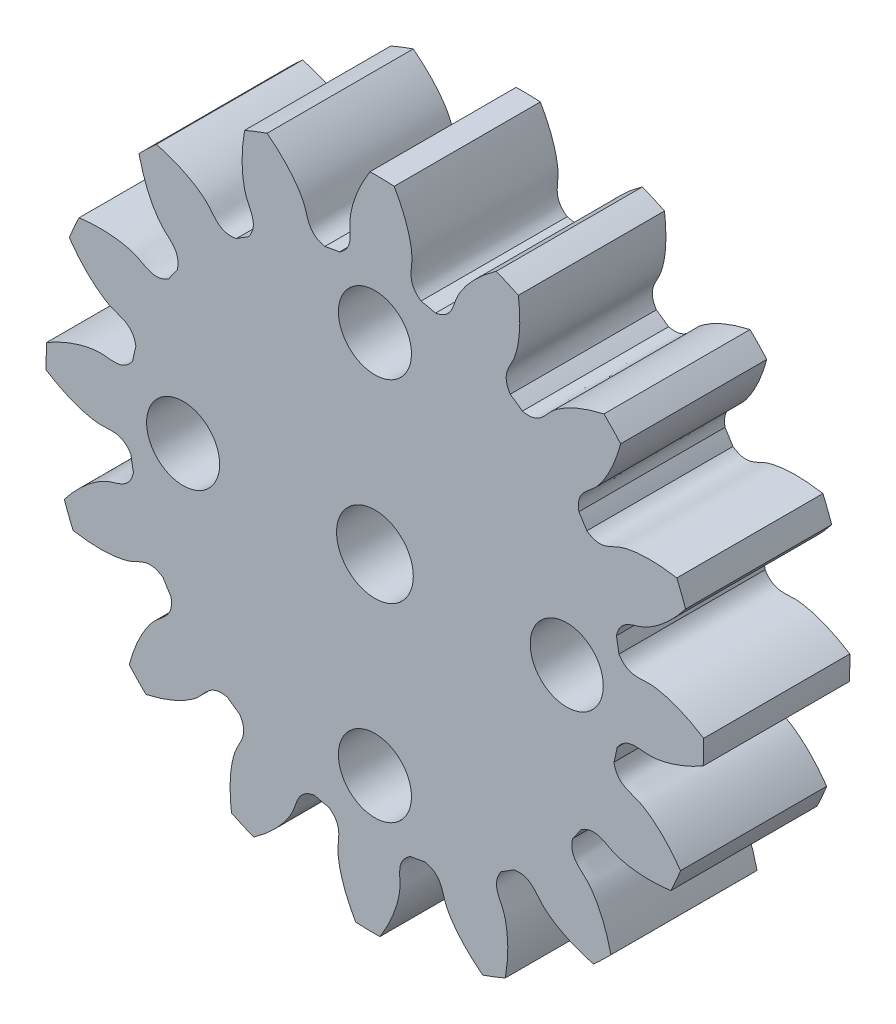
SolidWorks part; units mm, degrees
ref_plane "前视基准面" through (0, 0, 0) normal (0, 0, 1) x (1, 0, 0)
ref_plane "上视基准面" through (0, 0, 0) normal (0, 1, 0) x (1, 0, 0)
ref_plane "右视基准面" through (0, 0, 0) normal (1, 0, 0) x (0, 0, -1)
sketch "草图1" plane through (0, 0, 0) normal (0, 0, 1) x (1, 0, 0)
  circle A135 centre (26.7499, -4.2787) radius 1
  circle A136 centre (31.9999, 0.9713) radius 1
  circle A137 centre (26.7499, 6.2213) radius 1
  circle A138 centre (21.4999, 0.9713) radius 1
  arc A139 (20.7698, 7.6973) -> (20.2911, 7.2391) centre (26.7499, 0.9713) ccw
  arc A140 (21.3397, 5.0078) -> (21.1065, 4.6746) centre (26.7499, 0.9713) ccw
  arc A141 (18.6511, 4.8969) -> (18.3842, 4.2903) centre (26.7499, 0.9713) ccw
  arc A142 (20.2069, 2.6302) -> (20.1188, 2.2331) centre (26.7499, 0.9713) ccw
  arc A143 (17.7653, 1.4988) -> (17.7509, 0.8362) centre (26.7499, 0.9713) ccw
  arc A144 (20.0701, 0) -> (20.1407, -0.4005) centre (26.7499, 0.9713) ccw
  arc A145 (18.2474, -1.9796) -> (18.4876, -2.5972) centre (26.7499, 0.9713) ccw
  arc A146 (20.9503, -2.4823) -> (21.1688, -2.8253) centre (26.7499, 0.9713) ccw
  arc A147 (20.0239, -5.0087) -> (20.4821, -5.4874) centre (26.7499, 0.9713) ccw
  arc A148 (22.7134, -4.4388) -> (23.0466, -4.6721) centre (26.7499, 0.9713) ccw
  arc A149 (22.8243, -7.1274) -> (23.4309, -7.3943) centre (26.7499, 0.9713) ccw
  arc A150 (25.091, -5.5717) -> (25.4881, -5.6597) centre (26.7499, 0.9713) ccw
  arc A151 (26.2224, -8.0132) -> (26.8849, -8.0277) centre (26.7499, 0.9713) ccw
  arc A152 (27.7212, -5.7084) -> (28.1217, -5.6378) centre (26.7499, 0.9713) ccw
  arc A153 (29.7008, -7.5312) -> (30.3184, -7.291) centre (26.7499, 0.9713) ccw
  arc A154 (30.2035, -4.8283) -> (30.5465, -4.6097) centre (26.7499, 0.9713) ccw
  arc A155 (32.7299, -5.7547) -> (33.2086, -5.2964) centre (26.7499, 0.9713) ccw
  arc A156 (32.16, -3.0651) -> (32.3933, -2.732) centre (26.7499, 0.9713) ccw
  arc A157 (34.8486, -2.9542) -> (35.1155, -2.3476) centre (26.7499, 0.9713) ccw
  arc A158 (33.2929, -0.6875) -> (33.3809, -0.2904) centre (26.7499, 0.9713) ccw
  arc A159 (35.7344, 0.4438) -> (35.7489, 1.1064) centre (26.7499, 0.9713) ccw
  arc A160 (33.4296, 1.9426) -> (33.359, 2.3432) centre (26.7499, 0.9713) ccw
  arc A161 (35.2523, 3.9222) -> (35.0122, 4.5399) centre (26.7499, 0.9713) ccw
  arc A162 (32.5494, 4.4249) -> (32.3309, 4.768) centre (26.7499, 0.9713) ccw
  arc A163 (33.4759, 6.9514) -> (33.0176, 7.4301) centre (26.7499, 0.9713) ccw
  arc A164 (30.7863, 6.3814) -> (30.4532, 6.6147) centre (26.7499, 0.9713) ccw
  arc A165 (30.6754, 9.0701) -> (30.0688, 9.337) centre (26.7499, 0.9713) ccw
  arc A166 (28.4087, 7.5143) -> (28.0116, 7.6023) centre (26.7499, 0.9713) ccw
  arc A167 (27.2773, 9.9559) -> (26.6148, 9.9703) centre (26.7499, 0.9713) ccw
  arc A168 (25.7785, 7.6511) -> (25.378, 7.5804) centre (26.7499, 0.9713) ccw
  arc A169 (23.799, 9.4738) -> (23.1813, 9.2336) centre (26.7499, 0.9713) ccw
  arc A170 (23.2963, 6.7709) -> (22.9532, 6.5524) centre (26.7499, 0.9713) ccw
  circle A171 centre (26.7499, 0.9713) radius 1.05
  spline S32 degree 3 poles (22.9532, 6.5524) (22.485, 6.4713) (22.3632, 6.7975) (22.1228, 7.0302) (22.0876, 7.0622) (22.0369, 7.1047) (21.9751, 7.1526) (21.9016, 7.2049) (21.816, 7.2609) (21.7179, 7.3196) (21.607, 7.38) (21.483, 7.4414) (21.3456, 7.5026) (21.1948, 7.5627) (21.0303, 7.6208) (20.887, 7.6651) (20.7985, 7.6896) (20.7698, 7.6973) knots 0 0 0 0 0.200958 0.205848 0.217584 0.231929 0.248881 0.268441 0.29061 0.315386 0.342771 0.372764 0.405364 0.440573 0.47839 0.518814 0.53812 0.53812 0.53812 0.53812
  spline S33 degree 3 poles (20.2911, 7.2391) (20.311, 7.1494) (20.3475, 7.0039) (20.407, 6.8086) (20.4605, 6.6553) (20.5157, 6.5154) (20.5716, 6.3888) (20.6272, 6.2754) (20.6815, 6.1748) (20.7337, 6.0869) (20.7827, 6.0112) (20.8279, 5.9473) (20.8682, 5.8948) (20.8986, 5.8582) (21.1206, 5.608) (21.4412, 5.472) (21.3397, 5.0078) knots 0 0 0 0 0.059731 0.097548 0.132756 0.165357 0.195349 0.222734 0.247511 0.269679 0.289239 0.306192 0.320536 0.332272 0.337162 0.53812 0.53812 0.53812 0.53812
  spline S34 degree 3 poles (21.1065, 4.6746) (20.7049, 4.4205) (20.4675, 4.6753) (20.1564, 4.7983) (20.1116, 4.8144) (20.0485, 4.8343) (19.9731, 4.8548) (19.8851, 4.8751) (19.7846, 4.894) (19.6716, 4.9107) (19.546, 4.9241) (19.4079, 4.9333) (19.2576, 4.9373) (19.0952, 4.9352) (18.921, 4.9259) (18.7717, 4.9119) (18.6805, 4.9008) (18.6511, 4.8969) knots 0 0 0 0 0.200958 0.205848 0.217584 0.231929 0.248881 0.268441 0.29061 0.315386 0.342771 0.372764 0.405364 0.440573 0.47839 0.518814 0.53812 0.53812 0.53812 0.53812
  spline S35 degree 3 poles (18.3842, 4.2903) (18.4369, 4.2151) (18.5263, 4.0946) (18.656, 3.937) (18.7641, 3.8158) (18.8686, 3.7077) (18.9687, 3.6121) (19.0634, 3.5286) (19.1521, 3.4565) (19.234, 3.3952) (19.3083, 3.344) (19.3744, 3.3023) (19.4317, 3.2692) (19.4739, 3.2471) (19.7747, 3.1008) (20.1229, 3.0979) (20.2069, 2.6302) knots 0 0 0 0 0.059731 0.097548 0.132756 0.165357 0.195349 0.222734 0.247511 0.269679 0.289239 0.306192 0.320536 0.332272 0.337162 0.53812 0.53812 0.53812 0.53812
  spline S36 degree 3 poles (20.1188, 2.2331) (19.8451, 1.8446) (19.5283, 1.9892) (19.1938, 1.9838) (19.1462, 1.9815) (19.0803, 1.9757) (19.0028, 1.9659) (18.9138, 1.9509) (18.8137, 1.9299) (18.7029, 1.9021) (18.5817, 1.8664) (18.4506, 1.8221) (18.3102, 1.7683) (18.161, 1.7041) (18.0036, 1.6289) (17.871, 1.5588) (17.791, 1.5136) (17.7653, 1.4988) knots 0 0 0 0 0.200958 0.205848 0.217584 0.231929 0.248881 0.268441 0.29061 0.315386 0.342771 0.372764 0.405364 0.440573 0.47839 0.518814 0.53812 0.53812 0.53812 0.53812
  spline S37 degree 3 poles (17.7509, 0.8362) (17.8283, 0.7869) (17.9571, 0.7099) (18.1372, 0.6139) (18.2835, 0.5433) (18.4214, 0.4834) (18.5504, 0.4334) (18.6699, 0.3925) (18.7794, 0.3598) (18.8785, 0.3345) (18.9668, 0.3157) (19.0438, 0.3024) (19.1094, 0.2938) (19.1568, 0.2894) (19.4908, 0.2695) (19.8136, 0.4) (20.0701, 0) knots 0 0 0 0 0.059731 0.097548 0.132756 0.165357 0.195349 0.222734 0.247511 0.269679 0.289239 0.306192 0.320536 0.332272 0.337162 0.53812 0.53812 0.53812 0.53812
  spline S38 degree 3 poles (20.1407, -0.4005) (20.0365, -0.8642) (19.6885, -0.8519) (19.3815, -0.9849) (19.3385, -1.0052) (19.2798, -1.0357) (19.2119, -1.0745) (19.1354, -1.1224) (19.051, -1.1801) (18.9592, -1.2482) (18.8609, -1.3276) (18.7568, -1.4187) (18.6477, -1.5221) (18.5344, -1.6385) (18.4177, -1.7682) (18.322, -1.8837) (18.2655, -1.956) (18.2474, -1.9796) knots 0 0 0 0 0.200958 0.205848 0.217584 0.231929 0.248881 0.268441 0.29061 0.315386 0.342771 0.372764 0.405364 0.440573 0.47839 0.518814 0.53812 0.53812 0.53812 0.53812
  spline S39 degree 3 poles (18.4876, -2.5972) (18.578, -2.6132) (18.7264, -2.6351) (18.9296, -2.6548) (19.0917, -2.6641) (19.2421, -2.6666) (19.3804, -2.6635) (19.5065, -2.6555) (19.6202, -2.6438) (19.7214, -2.6293) (19.8101, -2.6129) (19.8864, -2.5957) (19.9503, -2.5785) (19.9958, -2.5644) (20.3119, -2.4551) (20.5602, -2.2109) (20.9503, -2.4823) knots 0 0 0 0 0.059731 0.097548 0.132756 0.165357 0.195349 0.222734 0.247511 0.269679 0.289239 0.306192 0.320536 0.332272 0.337162 0.53812 0.53812 0.53812 0.53812
  spline S40 degree 3 poles (21.1688, -2.8253) (21.2499, -3.2936) (20.9237, -3.4154) (20.691, -3.6557) (20.659, -3.6909) (20.6165, -3.7416) (20.5686, -3.8035) (20.5163, -3.877) (20.4603, -3.9626) (20.4016, -4.0606) (20.3412, -4.1715) (20.2798, -4.2956) (20.2186, -4.4329) (20.1585, -4.5838) (20.1004, -4.7483) (20.0561, -4.8916) (20.0315, -4.98) (20.0239, -5.0087) knots 0 0 0 0 0.200958 0.205848 0.217584 0.231929 0.248881 0.268441 0.29061 0.315386 0.342771 0.372764 0.405364 0.440573 0.47839 0.518814 0.53812 0.53812 0.53812 0.53812
  spline S41 degree 3 poles (20.4821, -5.4874) (20.5718, -5.4676) (20.7173, -5.431) (20.9126, -5.3715) (21.0659, -5.318) (21.2058, -5.2628) (21.3324, -5.207) (21.4458, -5.1514) (21.5463, -5.097) (21.6343, -5.0449) (21.71, -4.9958) (21.7739, -4.9507) (21.8264, -4.9104) (21.863, -4.8799) (22.1132, -4.6579) (22.2491, -4.3374) (22.7134, -4.4388) knots 0 0 0 0 0.059731 0.097548 0.132756 0.165357 0.195349 0.222734 0.247511 0.269679 0.289239 0.306192 0.320536 0.332272 0.337162 0.53812 0.53812 0.53812 0.53812
  spline S42 degree 3 poles (23.0466, -4.6721) (23.3007, -5.0736) (23.0459, -5.311) (22.9229, -5.6221) (22.9068, -5.6669) (22.8869, -5.73) (22.8663, -5.8055) (22.8461, -5.8934) (22.8272, -5.9939) (22.8105, -6.107) (22.7971, -6.2326) (22.7879, -6.3706) (22.7839, -6.5209) (22.786, -6.6833) (22.7953, -6.8575) (22.8093, -7.0069) (22.8204, -7.098) (22.8243, -7.1274) knots 0 0 0 0 0.200958 0.205848 0.217584 0.231929 0.248881 0.268441 0.29061 0.315386 0.342771 0.372764 0.405364 0.440573 0.47839 0.518814 0.53812 0.53812 0.53812 0.53812
  spline S43 degree 3 poles (23.4309, -7.3943) (23.5061, -7.3417) (23.6266, -7.2522) (23.7842, -7.1225) (23.9054, -7.0144) (24.0135, -6.9099) (24.1091, -6.8099) (24.1926, -6.7151) (24.2647, -6.6264) (24.326, -6.5446) (24.3772, -6.4702) (24.4189, -6.4041) (24.452, -6.3468) (24.4741, -6.3047) (24.6204, -6.0038) (24.6233, -5.6556) (25.091, -5.5717) knots 0 0 0 0 0.059731 0.097548 0.132756 0.165357 0.195349 0.222734 0.247511 0.269679 0.289239 0.306192 0.320536 0.332272 0.337162 0.53812 0.53812 0.53812 0.53812
  spline S44 degree 3 poles (25.4881, -5.6597) (25.8765, -5.9334) (25.732, -6.2503) (25.7374, -6.5847) (25.7397, -6.6323) (25.7454, -6.6982) (25.7553, -6.7758) (25.7703, -6.8648) (25.7913, -6.9648) (25.8191, -7.0757) (25.8548, -7.1969) (25.8991, -7.3279) (25.9529, -7.4683) (26.0171, -7.6176) (26.0923, -7.7749) (26.1624, -7.9076) (26.2076, -7.9875) (26.2224, -8.0132) knots 0 0 0 0 0.200958 0.205848 0.217584 0.231929 0.248881 0.268441 0.29061 0.315386 0.342771 0.372764 0.405364 0.440573 0.47839 0.518814 0.53812 0.53812 0.53812 0.53812
  spline S45 degree 3 poles (26.8849, -8.0277) (26.9343, -7.9502) (27.0113, -7.8215) (27.1073, -7.6413) (27.1779, -7.4951) (27.2378, -7.3571) (27.2878, -7.2281) (27.3287, -7.1086) (27.3614, -6.9991) (27.3867, -6.9) (27.4055, -6.8118) (27.4188, -6.7347) (27.4274, -6.6691) (27.4317, -6.6217) (27.4517, -6.2878) (27.3212, -5.965) (27.7212, -5.7084) knots 0 0 0 0 0.059731 0.097548 0.132756 0.165357 0.195349 0.222734 0.247511 0.269679 0.289239 0.306192 0.320536 0.332272 0.337162 0.53812 0.53812 0.53812 0.53812
  spline S46 degree 3 poles (28.1217, -5.6378) (28.5854, -5.7421) (28.5731, -6.0901) (28.7061, -6.397) (28.7264, -6.4401) (28.7569, -6.4988) (28.7957, -6.5667) (28.8436, -6.6431) (28.9013, -6.7276) (28.9694, -6.8193) (29.0487, -6.9176) (29.1399, -7.0218) (29.2433, -7.1309) (29.3597, -7.2442) (29.4894, -7.3608) (29.6049, -7.4565) (29.6772, -7.5131) (29.7008, -7.5312) knots 0 0 0 0 0.200958 0.205848 0.217584 0.231929 0.248881 0.268441 0.29061 0.315386 0.342771 0.372764 0.405364 0.440573 0.47839 0.518814 0.53812 0.53812 0.53812 0.53812
  spline S47 degree 3 poles (30.3184, -7.291) (30.3344, -7.2005) (30.3563, -7.0521) (30.376, -6.849) (30.3853, -6.6868) (30.3878, -6.5364) (30.3847, -6.3981) (30.3767, -6.2721) (30.365, -6.1584) (30.3505, -6.0572) (30.3341, -5.9684) (30.3169, -5.8921) (30.2997, -5.8282) (30.2856, -5.7828) (30.1763, -5.4666) (29.9321, -5.2183) (30.2035, -4.8283) knots 0 0 0 0 0.059731 0.097548 0.132756 0.165357 0.195349 0.222734 0.247511 0.269679 0.289239 0.306192 0.320536 0.332272 0.337162 0.53812 0.53812 0.53812 0.53812
  spline S48 degree 3 poles (30.5465, -4.6097) (31.0147, -4.5286) (31.1366, -4.8548) (31.3769, -5.0875) (31.4121, -5.1196) (31.4628, -5.1621) (31.5247, -5.21) (31.5981, -5.2623) (31.6837, -5.3182) (31.7818, -5.3769) (31.8927, -5.4374) (32.0167, -5.4987) (32.1541, -5.5599) (32.305, -5.6201) (32.4694, -5.6782) (32.6128, -5.7224) (32.7012, -5.747) (32.7299, -5.7547) knots 0 0 0 0 0.200958 0.205848 0.217584 0.231929 0.248881 0.268441 0.29061 0.315386 0.342771 0.372764 0.405364 0.440573 0.47839 0.518814 0.53812 0.53812 0.53812 0.53812
  spline S49 degree 3 poles (33.2086, -5.2964) (33.1887, -5.2068) (33.1522, -5.0613) (33.0927, -4.866) (33.0392, -4.7127) (32.984, -4.5728) (32.9281, -4.4462) (32.8726, -4.3328) (32.8182, -4.2322) (32.7661, -4.1443) (32.717, -4.0685) (32.6719, -4.0047) (32.6316, -3.9522) (32.6011, -3.9156) (32.3791, -3.6653) (32.0585, -3.5294) (32.16, -3.0651) knots 0 0 0 0 0.059731 0.097548 0.132756 0.165357 0.195349 0.222734 0.247511 0.269679 0.289239 0.306192 0.320536 0.332272 0.337162 0.53812 0.53812 0.53812 0.53812
  spline S50 degree 3 poles (32.3933, -2.732) (32.7948, -2.4779) (33.0322, -2.7326) (33.3433, -2.8556) (33.3881, -2.8717) (33.4512, -2.8916) (33.5267, -2.9122) (33.6146, -2.9324) (33.7151, -2.9514) (33.8282, -2.968) (33.9538, -2.9815) (34.0918, -2.9907) (34.2421, -2.9947) (34.4045, -2.9925) (34.5787, -2.9832) (34.7281, -2.9693) (34.8192, -2.9581) (34.8486, -2.9542) knots 0 0 0 0 0.200958 0.205848 0.217584 0.231929 0.248881 0.268441 0.29061 0.315386 0.342771 0.372764 0.405364 0.440573 0.47839 0.518814 0.53812 0.53812 0.53812 0.53812
  spline S51 degree 3 poles (35.1155, -2.3476) (35.0629, -2.2724) (34.9734, -2.152) (34.8437, -1.9944) (34.7356, -1.8732) (34.6311, -1.765) (34.531, -1.6695) (34.4363, -1.5859) (34.3476, -1.5138) (34.2658, -1.4526) (34.1914, -1.4014) (34.1253, -1.3596) (34.068, -1.3266) (34.0258, -1.3044) (33.725, -1.1582) (33.3768, -1.1553) (33.2929, -0.6875) knots 0 0 0 0 0.059731 0.097548 0.132756 0.165357 0.195349 0.222734 0.247511 0.269679 0.289239 0.306192 0.320536 0.332272 0.337162 0.53812 0.53812 0.53812 0.53812
  spline S52 degree 3 poles (33.3809, -0.2904) (33.6546, 0.098) (33.9714, -0.0465) (34.3059, -0.0411) (34.3535, -0.0389) (34.4194, -0.0331) (34.497, -0.0232) (34.5859, -0.0083) (34.686, 0.0127) (34.7969, 0.0406) (34.9181, 0.0762) (35.0491, 0.1206) (35.1895, 0.1744) (35.3387, 0.2385) (35.4961, 0.3138) (35.6288, 0.3838) (35.7087, 0.429) (35.7344, 0.4438) knots 0 0 0 0 0.200958 0.205848 0.217584 0.231929 0.248881 0.268441 0.29061 0.315386 0.342771 0.372764 0.405364 0.440573 0.47839 0.518814 0.53812 0.53812 0.53812 0.53812
  spline S53 degree 3 poles (35.7489, 1.1064) (35.6714, 1.1557) (35.5427, 1.2328) (35.3625, 1.3288) (35.2163, 1.3994) (35.0783, 1.4593) (34.9493, 1.5093) (34.8298, 1.5502) (34.7203, 1.5829) (34.6212, 1.6082) (34.533, 1.627) (34.4559, 1.6403) (34.3903, 1.6489) (34.3429, 1.6532) (34.009, 1.6732) (33.6862, 1.5426) (33.4296, 1.9426) knots 0 0 0 0 0.059731 0.097548 0.132756 0.165357 0.195349 0.222734 0.247511 0.269679 0.289239 0.306192 0.320536 0.332272 0.337162 0.53812 0.53812 0.53812 0.53812
  spline S54 degree 3 poles (33.359, 2.3432) (33.4633, 2.8068) (33.8112, 2.7945) (34.1182, 2.9275) (34.1613, 2.9478) (34.22, 2.9784) (34.2879, 3.0172) (34.3643, 3.0651) (34.4488, 3.1227) (34.5405, 3.1909) (34.6388, 3.2702) (34.7429, 3.3613) (34.8521, 3.4648) (34.9654, 3.5811) (35.082, 3.7109) (35.1777, 3.8263) (35.2343, 3.8987) (35.2523, 3.9222) knots 0 0 0 0 0.200958 0.205848 0.217584 0.231929 0.248881 0.268441 0.29061 0.315386 0.342771 0.372764 0.405364 0.440573 0.47839 0.518814 0.53812 0.53812 0.53812 0.53812
  spline S55 degree 3 poles (35.0122, 4.5399) (34.9217, 4.5558) (34.7733, 4.5777) (34.5701, 4.5975) (34.408, 4.6067) (34.2576, 4.6093) (34.1193, 4.6061) (33.9932, 4.5982) (33.8796, 4.5865) (33.7783, 4.5719) (33.6896, 4.5555) (33.6133, 4.5383) (33.5494, 4.5212) (33.504, 4.507) (33.1878, 4.3977) (32.9395, 4.1536) (32.5494, 4.4249) knots 0 0 0 0 0.059731 0.097548 0.132756 0.165357 0.195349 0.222734 0.247511 0.269679 0.289239 0.306192 0.320536 0.332272 0.337162 0.53812 0.53812 0.53812 0.53812
  spline S56 degree 3 poles (32.3309, 4.768) (32.2498, 5.2362) (32.576, 5.358) (32.8087, 5.5984) (32.8407, 5.6336) (32.8833, 5.6843) (32.9311, 5.7461) (32.9835, 5.8196) (33.0394, 5.9052) (33.0981, 6.0033) (33.1586, 6.1142) (33.2199, 6.2382) (33.2811, 6.3756) (33.3413, 6.5264) (33.3994, 6.6909) (33.4436, 6.8342) (33.4682, 6.9227) (33.4759, 6.9514) knots 0 0 0 0 0.200958 0.205848 0.217584 0.231929 0.248881 0.268441 0.29061 0.315386 0.342771 0.372764 0.405364 0.440573 0.47839 0.518814 0.53812 0.53812 0.53812 0.53812
  spline S57 degree 3 poles (33.0176, 7.4301) (32.928, 7.4102) (32.7824, 7.3737) (32.5872, 7.3142) (32.4338, 7.2606) (32.2939, 7.2055) (32.1674, 7.1496) (32.0539, 7.094) (31.9534, 7.0397) (31.8654, 6.9875) (31.7897, 6.9384) (31.7259, 6.8933) (31.6734, 6.853) (31.6368, 6.8226) (31.3865, 6.6006) (31.2506, 6.28) (30.7863, 6.3814) knots 0 0 0 0 0.059731 0.097548 0.132756 0.165357 0.195349 0.222734 0.247511 0.269679 0.289239 0.306192 0.320536 0.332272 0.337162 0.53812 0.53812 0.53812 0.53812
  spline S58 degree 3 poles (30.4532, 6.6147) (30.1991, 7.0163) (30.4538, 7.2537) (30.5768, 7.5648) (30.5929, 7.6096) (30.6128, 7.6727) (30.6334, 7.7481) (30.6536, 7.8361) (30.6726, 7.9365) (30.6892, 8.0496) (30.7027, 8.1752) (30.7119, 8.3133) (30.7159, 8.4636) (30.7137, 8.626) (30.7044, 8.8002) (30.6905, 8.9495) (30.6793, 9.0407) (30.6754, 9.0701) knots 0 0 0 0 0.200958 0.205848 0.217584 0.231929 0.248881 0.268441 0.29061 0.315386 0.342771 0.372764 0.405364 0.440573 0.47839 0.518814 0.53812 0.53812 0.53812 0.53812
  spline S59 degree 3 poles (30.0688, 9.337) (29.9936, 9.2843) (29.8732, 9.1949) (29.7155, 9.0652) (29.5944, 8.9571) (29.4862, 8.8525) (29.3907, 8.7525) (29.3071, 8.6577) (29.235, 8.5691) (29.1737, 8.4872) (29.1226, 8.4129) (29.0808, 8.3468) (29.0478, 8.2895) (29.0256, 8.2473) (28.8794, 7.9465) (28.8764, 7.5983) (28.4087, 7.5143) knots 0 0 0 0 0.059731 0.097548 0.132756 0.165357 0.195349 0.222734 0.247511 0.269679 0.289239 0.306192 0.320536 0.332272 0.337162 0.53812 0.53812 0.53812 0.53812
  spline S60 degree 3 poles (28.0116, 7.6023) (27.6232, 7.8761) (27.7677, 8.1929) (27.7623, 8.5274) (27.76, 8.5749) (27.7543, 8.6409) (27.7444, 8.7184) (27.7294, 8.8074) (27.7085, 8.9075) (27.6806, 9.0183) (27.645, 9.1395) (27.6006, 9.2706) (27.5468, 9.411) (27.4827, 9.5602) (27.4074, 9.7176) (27.3374, 9.8502) (27.2922, 9.9301) (27.2773, 9.9559) knots 0 0 0 0 0.200958 0.205848 0.217584 0.231929 0.248881 0.268441 0.29061 0.315386 0.342771 0.372764 0.405364 0.440573 0.47839 0.518814 0.53812 0.53812 0.53812 0.53812
  spline S61 degree 3 poles (26.6148, 9.9703) (26.5655, 9.8929) (26.4884, 9.7641) (26.3924, 9.584) (26.3218, 9.4377) (26.2619, 9.2998) (26.2119, 9.1708) (26.171, 9.0513) (26.1383, 8.9418) (26.113, 8.8427) (26.0942, 8.7544) (26.0809, 8.6774) (26.0723, 8.6118) (26.068, 8.5643) (26.048, 8.2304) (26.1786, 7.9076) (25.7785, 7.6511) knots 0 0 0 0 0.059731 0.097548 0.132756 0.165357 0.195349 0.222734 0.247511 0.269679 0.289239 0.306192 0.320536 0.332272 0.337162 0.53812 0.53812 0.53812 0.53812
  spline S62 degree 3 poles (25.378, 7.5804) (24.9144, 7.6847) (24.9267, 8.0327) (24.7937, 8.3396) (24.7734, 8.3827) (24.7428, 8.4414) (24.704, 8.5093) (24.6561, 8.5858) (24.5985, 8.6702) (24.5303, 8.762) (24.451, 8.8603) (24.3599, 8.9644) (24.2564, 9.0735) (24.1401, 9.1868) (24.0103, 9.3034) (23.8948, 9.3992) (23.8225, 9.4557) (23.799, 9.4738) knots 0 0 0 0 0.200958 0.205848 0.217584 0.231929 0.248881 0.268441 0.29061 0.315386 0.342771 0.372764 0.405364 0.440573 0.47839 0.518814 0.53812 0.53812 0.53812 0.53812
  spline S63 degree 3 poles (23.1813, 9.2336) (23.1654, 9.1432) (23.1434, 8.9948) (23.1237, 8.7916) (23.1145, 8.6294) (23.1119, 8.4791) (23.1151, 8.3408) (23.123, 8.2147) (23.1347, 8.101) (23.1493, 7.9998) (23.1656, 7.9111) (23.1829, 7.8348) (23.2, 7.7709) (23.2142, 7.7254) (23.3235, 7.4093) (23.5676, 7.161) (23.2963, 6.7709) knots 0 0 0 0 0.059731 0.097548 0.132756 0.165357 0.195349 0.222734 0.247511 0.269679 0.289239 0.306192 0.320536 0.332272 0.337162 0.53812 0.53812 0.53812 0.53812
  dimension "D1" = 10.5
  dimension "D2" = 2.1
extrude "凸台-拉伸1" add sketch "草图1" along normal blind 4
